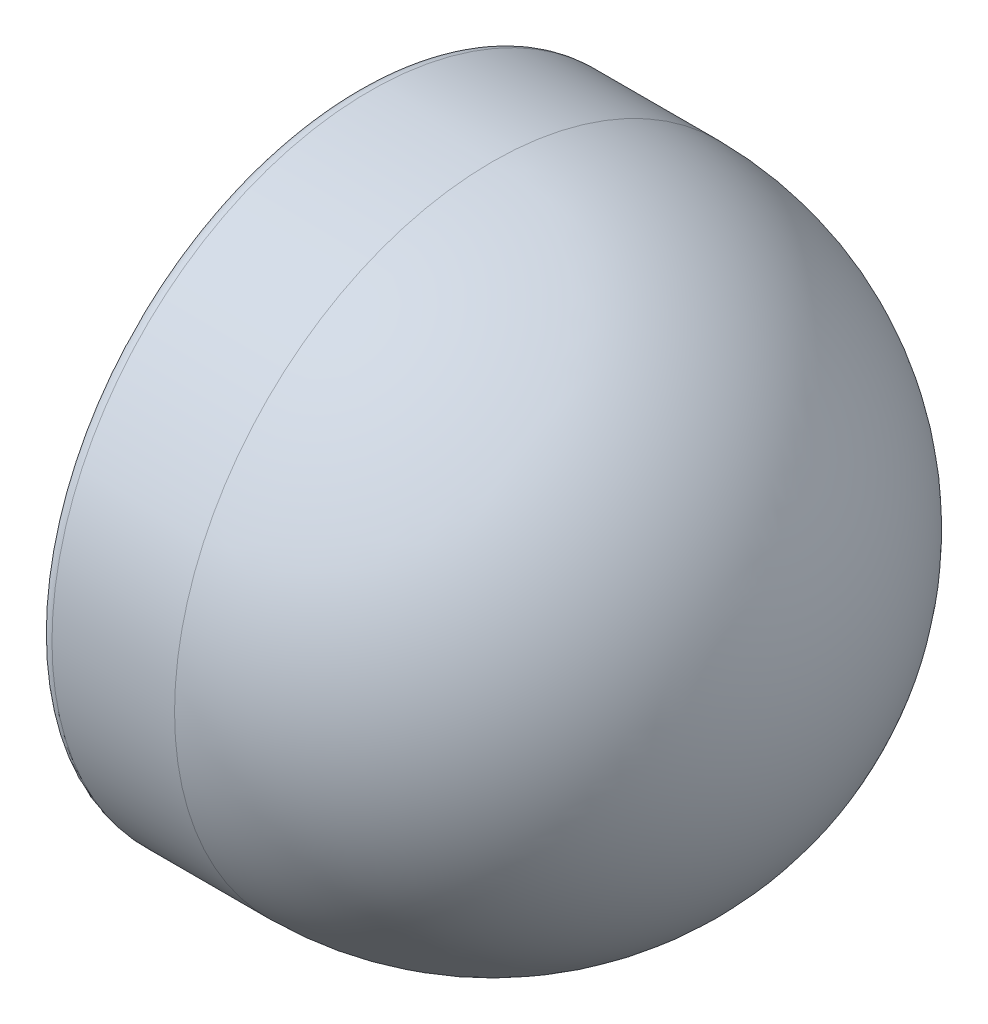
SolidWorks part; units mm, degrees
ref_plane "Płaszczyzna przednia" through (0, 0, 0) normal (0, 0, 1) x (1, 0, 0)
ref_plane "Płaszczyzna górna" through (0, 0, 0) normal (0, 1, 0) x (1, 0, 0)
ref_plane "Płaszczyzna prawa" through (0, 0, 0) normal (1, 0, 0) x (0, 0, -1)
sketch "Szkic1" plane through (0, 0, 0) normal (0, 0, 1) x (1, 0, 0)
  line L0 (-70, 0) -> (174.2262, 0) construction
  line L1 (-70, 70) -> (-97, 70)
  line L2 (-100, 67) -> (-100, 61.5)
  line L3 (-98.5, 60) -> (-96.6213, 60)
  line L4 (-95.5607, 60.4393) -> (-92, 64)
  line L5 (-70, 69) -> (-97, 69)
  line L6 (-99, 67) -> (-99, 61.5)
  line L7 (-98.5, 61) -> (-96.6213, 61)
  line L8 (-96.2678, 61.1464) -> (-92.7071, 64.7071)
  line L9 (-92, 64) -> (-92, 64.7071)
  line L10 (-92, 64.7071) -> (-92.7071, 64.7071)
  line L11 (-1, 0) -> (0, 0)
  arc A0 (0, 0) -> (-70, 70) centre (-70, 0) ccw
  arc A1 (-97, 70) -> (-100, 67) centre (-97, 67) ccw
  arc A2 (-100, 61.5) -> (-98.5, 60) centre (-98.5, 61.5) ccw
  arc A3 (-96.6213, 60) -> (-95.5607, 60.4393) centre (-96.6213, 61.5) ccw
  arc A4 (-1, 0) -> (-70, 69) centre (-70, 0) ccw
  arc A5 (-97, 69) -> (-99, 67) centre (-97, 67) ccw
  arc A6 (-99, 61.5) -> (-98.5, 61) centre (-98.5, 61.5) ccw
  arc A7 (-96.6213, 61) -> (-96.2678, 61.1464) centre (-96.6213, 61.5) ccw
  point P12 (-100, 70)
  point P15 (-100, 60)
  point P18 (-96, 60)
  dimension "D1" = 70
  dimension "D6" = 3
  dimension "D7" = 1.5
  dimension "D8" = 1.5
  dimension "D2" = 30
  dimension "D3" = 10
  dimension "D4" = 4
  dimension "D5" = 135
  dimension "D10" = 7
  dimension "D9" = 1
revolve "Obrót1" add sketch "Szkic1" angle 360 about L0
